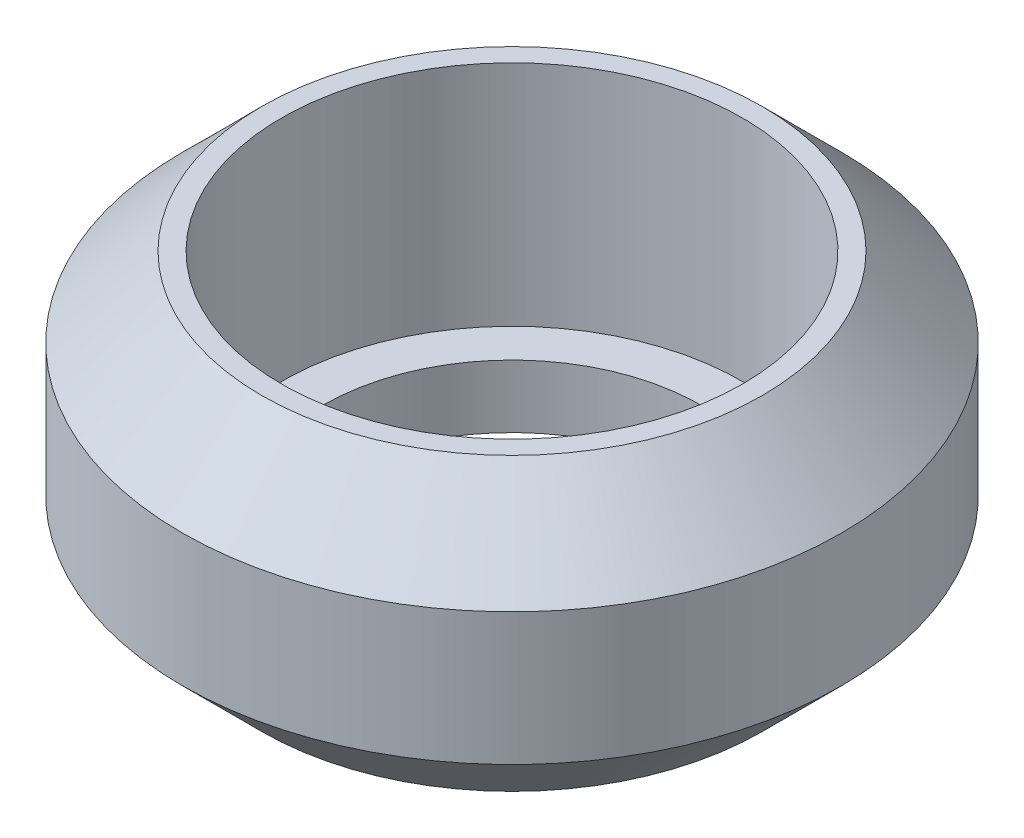
SolidWorks part; units mm, degrees
material "ABS"
ref_plane "Front Plane" through (0, 0, 0) normal (0, 0, 1) x (1, 0, 0)
ref_plane "Top Plane" through (0, 0, 0) normal (0, 1, 0) x (1, 0, 0)
ref_plane "Right Plane" through (0, 0, 0) normal (1, 0, 0) x (0, 0, -1)
sketch "Roller Profile Sketch" plane through (0, 0, 0) normal (0, 0, 1) x (1, 0, 0)
  line L0 (0, -6.35) -> (0, 6.35)
  line L1 (0, 0) -> (-6.35, 0) construction
  line L2 (-6.35, 0) -> (0, 6.35)
  line L3 (-6.35, 0) -> (0, -6.35)
  line L4 (-0.762, 5.588) -> (-0.762, -5.588) construction
  line L5 (0, 0) -> (8.8519, 0) construction
  line L6 (-0.762, 5.588) -> (0, 5.588)
  line L7 (-0.762, -5.588) -> (0, -5.588)
  line L8 (8.8519, -5.81) -> (8.8519, 5.81) construction
  line L9 (-2.286, 4.064) -> (-2.286, -4.064) construction
  line L10 (-3.81, 2.54) -> (-3.81, -2.54)
  line L11 (-0.762, -5.588) -> (1.5875, -5.588)
  line L12 (1.5875, -5.588) -> (1.5875, -3.175)
  line L13 (1.5875, -3.175) -> (0, -3.175)
  point P4 (0, 0)
  point P14 (8.8519, 0)
  dimension "D1" = 6.35
  dimension "D2" = 45
  dimension "D3" = 11.176
  dimension "D4" = 8.8519
  dimension "D5" = 8.128
  dimension "D6" = 2.54
  dimension "D7" = 3.175
  dimension "D8" = 1.5875
revolve "Revolve" add sketch "Roller Profile Sketch" angle 360 about L8
equation "\"bearing diameter\"= 0.687"
equation "\"bearing thickness\"= 0.25"
equation "\"track opening\"=0.32"
equation "\"track depth\"= 0.315 + 0.16"
equation "\"roller angle\"= 45"
equation "\"roller thickness\"= 0.25"
equation "\"extra thickness\"= 0.12"
equation "\"D3@Roller Profile Sketch\" = \"track opening\" + \"extra thickness\""
equation "\"D2@Roller Profile Sketch\" = \"roller angle\""
equation "\"D1@Roller Profile Sketch\" = \"roller thickness\""
equation "\"D4@Roller Profile Sketch\"=\"bearing diameter\" / 2 + \"bearing tolerance\""
equation "\"D5@Roller Profile Sketch\"=\"track opening\""
equation "\"tip cut\"= 0.1"
equation "\"lip inset\"= 1 / 16"
equation "\"D7@Roller Profile Sketch\"=\"bearing thickness\"/2"
equation "\"D8@Roller Profile Sketch\"=\"lip inset\""
equation "\"D6@Roller Profile Sketch\"=\"tip cut\""
equation "\"bearing tolerance\"= 0.005"
